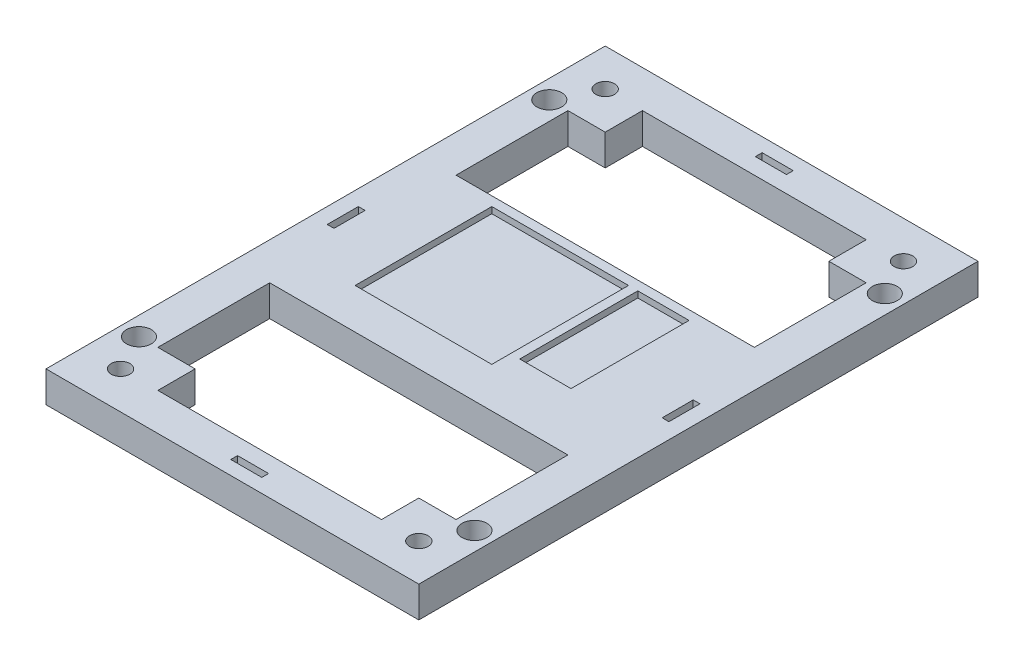
SolidWorks part; units mm, degrees
material "Acrylic (Medium-high impact)"
ref_plane "Front Plane" through (0, 0, 0) normal (0, 0, 1) x (1, 0, 0)
ref_plane "Top Plane" through (0, 0, 0) normal (0, 1, 0) x (1, 0, 0)
ref_plane "Right Plane" through (0, 0, 0) normal (1, 0, 0) x (0, 0, -1)
sketch "Sketch1" plane through (0, 0, 0) normal (0, 1, 0) x (1, 0, 0)
  line L0 (-175, -150) -> (-55, -150)
  line L1 (-55, -150) -> (-55, 30)
  line L2 (-55, 30) -> (-175, 30)
  line L3 (-175, 30) -> (-175, -150)
  line L4 (-163, 6) -> (-163, -126)
  line L5 (-151, -138) -> (-79, -138)
  line L6 (-67, -126) -> (-67, 6)
  line L7 (-79, 18) -> (-151, 18)
  line L8 (-163, 6) -> (-151, 6)
  line L9 (-151, 6) -> (-151, 18)
  line L10 (-79, 18) -> (-79, 6)
  line L11 (-79, 6) -> (-67, 6)
  line L12 (-67, -126) -> (-79, -126)
  line L13 (-79, -126) -> (-79, -138)
  line L14 (-163, -126) -> (-151, -126)
  line L15 (-151, -126) -> (-151, -138)
  line L16 (-115, -150) -> (-115, 30) construction
  line L17 (-55, -60) -> (-251.1486, -60) construction
  circle A0 centre (-163, -138) radius 3
  circle A1 centre (-67, -138) radius 3
  circle A2 centre (-163, 18) radius 3
  circle A3 centre (-67, 18) radius 3
  dimension "D16" = 6
  dimension "D2" = 180
  dimension "D3" = 12
  dimension "D4" = 12
  dimension "D5" = 12
  dimension "D6" = 12
  dimension "D7" = 12
  dimension "D8" = 12
  dimension "D9" = 12
  dimension "D10" = 12
  dimension "D11" = 12
  dimension "D12" = 12
  dimension "D13" = 12
  dimension "D14" = 12
  dimension "D15" = 12
  dimension "D17" = 120
extrude "Boss-Extrude1" add sketch "Sketch1" along normal blind 10
sketch "Sketch2" plane through (0, 0, 0) normal (0, 1, 0) x (1, 0, 0)
  line L0 (-163, -30) -> (-67, -30)
  line L1 (-175, -150) -> (-55, -150) construction
  line L2 (-163, -30) -> (-163, -90)
  line L3 (-163, 6) -> (-163, -126) construction
  line L4 (-67, -126) -> (-67, 6) construction
  line L5 (-67, -90) -> (-67, -30)
  line L6 (-163, -90) -> (-67, -90)
  point P1 (-163, -60)
  dimension "D1" = 90
  dimension "D2" = 60
  dimension "D3" = 60
extrude "Boss-Extrude2" add sketch "Sketch2" along normal blind 10
sketch "Sketch8" plane through (0, 10, 0) normal (0, 1, 0) x (1, 0, 0)
  line L0 (-175, 30) -> (-175, -150) construction
  line L1 (-169.9876, -54.4793) -> (-167.8096, -54.4793)
  line L2 (-169.9876, -54.4793) -> (-169.9876, -64.4793)
  line L3 (-169.9876, -64.4793) -> (-167.8096, -64.4793)
  line L4 (-167.8096, -54.4793) -> (-167.8096, -64.4793)
  line L5 (-169.9876, -54.4793) -> (-167.8096, -64.4793) construction
  line L6 (-169.9876, -64.4793) -> (-167.8096, -54.4793) construction
  line L7 (-151, 6) -> (-163, 6) construction
  line L8 (-115, -150) -> (-115, 65.8581) construction
  line L9 (-175, -150) -> (-110, -150) construction
  line L10 (-55, -60) -> (-196.2044, -60) construction
  line L15 (-175, -150) -> (-55, -150) construction
  line L16 (-60.0124, -64.4793) -> (-62.1904, -54.4793) construction
  line L21 (-120, 25.5242) -> (-110, 25.5242)
  line L22 (-120, 25.5242) -> (-120, 23.3442)
  line L23 (-120, 23.3442) -> (-110, 23.3442)
  line L24 (-110, 25.5242) -> (-110, 23.3442)
  line L25 (-120, 25.5242) -> (-110, 23.3442) construction
  line L26 (-120, 23.3442) -> (-110, 25.5242) construction
  line L28 (-60.0124, -54.4793) -> (-62.1904, -64.4793) construction
  line L37 (-62.1904, -54.4793) -> (-62.1904, -64.4793)
  line L38 (-60.0124, -64.4793) -> (-62.1904, -64.4793)
  line L39 (-60.0124, -54.4793) -> (-60.0124, -64.4793)
  line L40 (-60.0124, -54.4793) -> (-62.1904, -54.4793)
  line L41 (-55, -150) -> (-55, 30) construction
  line L42 (-120, -143.3442) -> (-110, -145.5242) construction
  line L43 (-120, -145.5242) -> (-110, -143.3442) construction
  line L44 (-110, -145.5242) -> (-110, -143.3442)
  line L45 (-120, -143.3442) -> (-110, -143.3442)
  line L46 (-120, -145.5242) -> (-120, -143.3442)
  line L47 (-120, -145.5242) -> (-110, -145.5242)
  circle A0 centre (-169, 6) radius 4
  circle A1 centre (-169, -126.0777) radius 4
  circle A8 centre (-61, -126.0777) radius 4
  circle A9 centre (-61, 6) radius 4
  point P0 (-168.8986, -59.4793)
  point P27 (-61.1014, -59.4793)
  point P30 (-115, 24.4342)
  point P42 (-115, -144.4342)
  dimension "D2" = 8
  dimension "D1" = 10
  dimension "D3" = 6
  dimension "D4" = 0
  dimension "D5" = 65
  dimension "D6" = 2.18
  dimension "D7" = 10
extrude "Cut-Extrude8" cut sketch "Sketch8" against normal through all
sketch "Sketch7" plane through (0, 10, 0) normal (0, 1, 0) x (1, 0, 0)
  line L1 (-101.5, -33) -> (-85, -33)
  line L2 (-101.5, -33) -> (-101.5, -71)
  line L3 (-101.5, -71) -> (-85, -71)
  line L4 (-85, -33) -> (-85, -71)
  line L5 (-101.5, -33) -> (-85, -71) construction
  line L6 (-101.5, -71) -> (-85, -33) construction
  line L9 (-55, -150) -> (-55, 30) construction
  line L10 (-67, -30) -> (-163, -30) construction
  line L11 (-115.0388, 30) -> (-115.0388, -212.6734) construction
  point P0 (-93.25, -52)
  dimension "D1" = 38
  dimension "D2" = 16.5
  dimension "D3" = 30
  dimension "D4" = 3
extrude "Cut-Extrude7" cut sketch "Sketch7" against normal blind 2
sketch "Sketch5" plane through (0, 10, 0) normal (0, 1, 0) x (1, 0, 0)
  line L0 (-67, -30) -> (-163, -30) construction
  line L1 (-148.5, -33) -> (-104.5, -33)
  line L2 (-148.5, -33) -> (-148.5, -77)
  line L3 (-148.5, -77) -> (-104.5, -77)
  line L4 (-104.5, -33) -> (-104.5, -77)
  line L5 (-148.5, -33) -> (-104.5, -77) construction
  line L6 (-148.5, -77) -> (-104.5, -33) construction
  line L8 (-101.5, -33) -> (-101.5, -71) construction
  point P0 (-126.5, -55)
  dimension "D1" = 44
  dimension "D2" = 44
  dimension "D3" = 3
  dimension "D4" = 3
extrude "Cut-Extrude5" cut sketch "Sketch5" against normal blind 2
